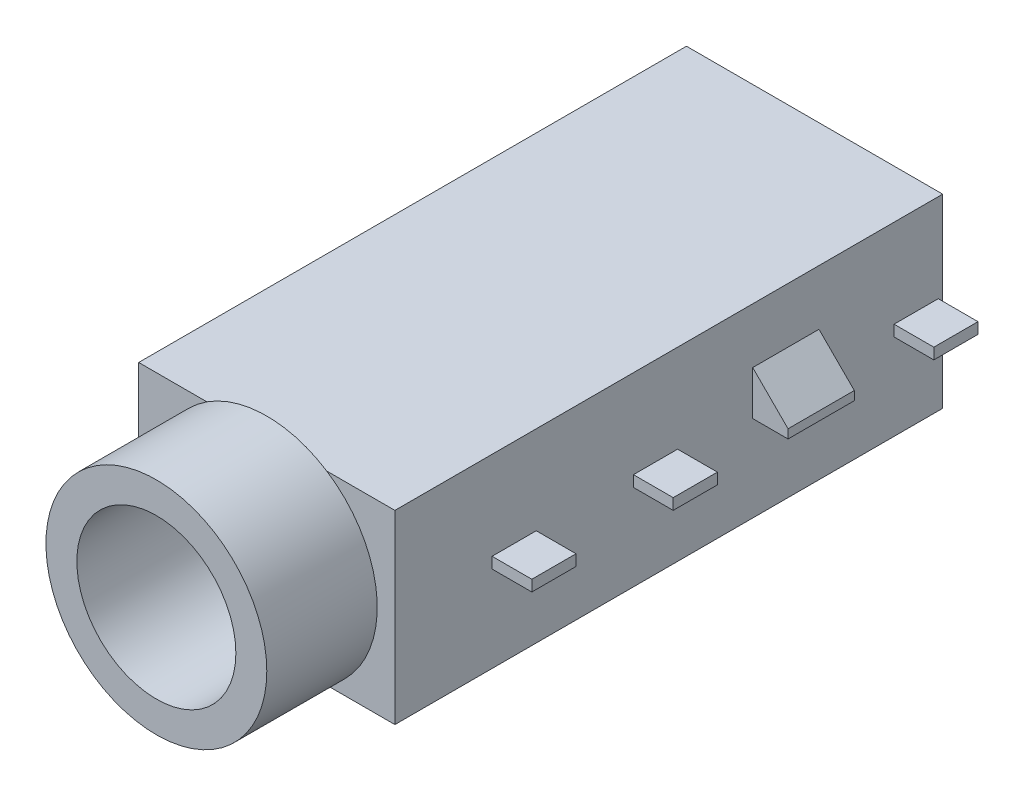
SolidWorks part; units mm, degrees
ref_plane "前视基准面" through (0, 0, 0) normal (0, 0, 1) x (1, 0, 0)
ref_plane "上视基准面" through (0, 0, 0) normal (0, 1, 0) x (1, 0, 0)
ref_plane "右视基准面" through (0, 0, 0) normal (1, 0, 0) x (0, 0, -1)
sketch "草图1" plane through (0, 0, 0) normal (0, 1, 0) x (1, 0, 0)
  line L1 (-2.9, 0) -> (2.9, 0)
  line L2 (-2.9, 0) -> (-2.9, 12.4)
  line L3 (-2.9, 12.4) -> (2.9, 12.4)
  line L4 (2.9, 0) -> (2.9, 12.4)
  line L5 (-2.9, 0) -> (2.9, 12.4) construction
  line L6 (-2.9, 12.4) -> (2.9, 0) construction
  point P0 (0, 6.2)
  point P7 (0, 0)
  dimension "D1" = 5.8
  dimension "D2" = 12.4
extrude "凸台-拉伸1" add sketch "草图1" along normal blind 4.2
sketch "草图2" plane through (0, 0, 0) normal (0, 0, 1) x (1, 0, 0)
  line L0 (-2.9, 4.2) -> (2.9, 0) construction
  line L1 (-2.9, 0) -> (2.9, 4.2) construction
  circle A0 centre (0, 2.1) radius 2.5
  point P13 (0, 2.1)
  dimension "D1" = 5
extrude "凸台-拉伸2" add sketch "草图2" along normal blind 2.5
sketch "草图4" plane through (2.9, 0, 0) normal (1, 0, 0) x (0, 0, -1)
  line L1 (2.2, 1.95) -> (3.2, 1.95)
  line L2 (2.2, 1.95) -> (2.2, 2.2)
  line L3 (2.2, 2.2) -> (3.2, 2.2)
  line L4 (3.2, 1.95) -> (3.2, 2.2)
  line L5 (0, 0) -> (12.4, 0) construction
  line L6 (5.4, 1.95) -> (6.4, 1.95)
  line L7 (5.4, 1.95) -> (5.4, 2.2)
  line L8 (5.4, 2.2) -> (6.4, 2.2)
  line L9 (6.4, 1.95) -> (6.4, 2.2)
  line L10 (11.3, 1.95) -> (12.3, 1.95)
  line L11 (11.3, 1.95) -> (11.3, 2.2)
  line L12 (11.3, 2.2) -> (12.3, 2.2)
  line L13 (12.3, 1.95) -> (12.3, 2.2)
  line L14 (0, 4.2) -> (0, 0) construction
  dimension "D1" = 1
  dimension "D2" = 1.95
  dimension "D3" = 2.2
  dimension "D4" = 3.2
  dimension "D5" = 0.25
  dimension "D6" = 5.9
extrude "凸台-拉伸4" add sketch "草图4" along normal blind 0.9
sketch "草图5" plane through (0, 0, 2.5) normal (0, 0, 1) x (1, 0, 0)
  circle A0 centre (0, 2.1) radius 1.8
  dimension "D1" = 3.6
extrude "切除-拉伸1" cut sketch "草图5" against normal through all
sketch "草图6" plane through (2.9, 0, 0) normal (1, 0, 0) x (0, 0, -1)
  line L0 (0, 4.2) -> (12.4, 4.2) construction
  line L1 (8.1, 1.95) -> (9.6, 1.95)
  line L2 (8.1, 1.95) -> (8.1, 2.95)
  line L3 (8.1, 2.95) -> (9.6, 2.95)
  line L4 (9.6, 1.95) -> (9.6, 2.95)
  line L5 (12.4, 4.2) -> (12.4, 0) construction
  dimension "D1" = 1.5
  dimension "D2" = 2.25
  dimension "D3" = 2.8
  dimension "D4" = 1
extrude "凸台-拉伸5" add sketch "草图6" along normal blind 0.8
sketch "草图7" plane through (0, 0, -9.6) normal (0, 0, -1) x (-1, 0, 0)
  line L0 (-3.7, 2.95) -> (-2.9, 2.95)
  line L1 (-3.7, 2.95) -> (-2.9, 2.95) construction
  line L2 (-2.9, 2.95) -> (-3.7, 2.15)
  line L3 (-3.7, 1.95) -> (-3.7, 2.95) construction
  line L4 (-3.7, 2.15) -> (-3.7, 2.95)
extrude "切除-拉伸2" cut sketch "草图7" against normal up to surface (1.5 mm away) up to face at (3.3, 2.45, -8.1)
mirror "镜向1" about plane through (0, 0, 0) normal (1, 0, 0) of "切除-拉伸2", "凸台-拉伸4", "凸台-拉伸5"
